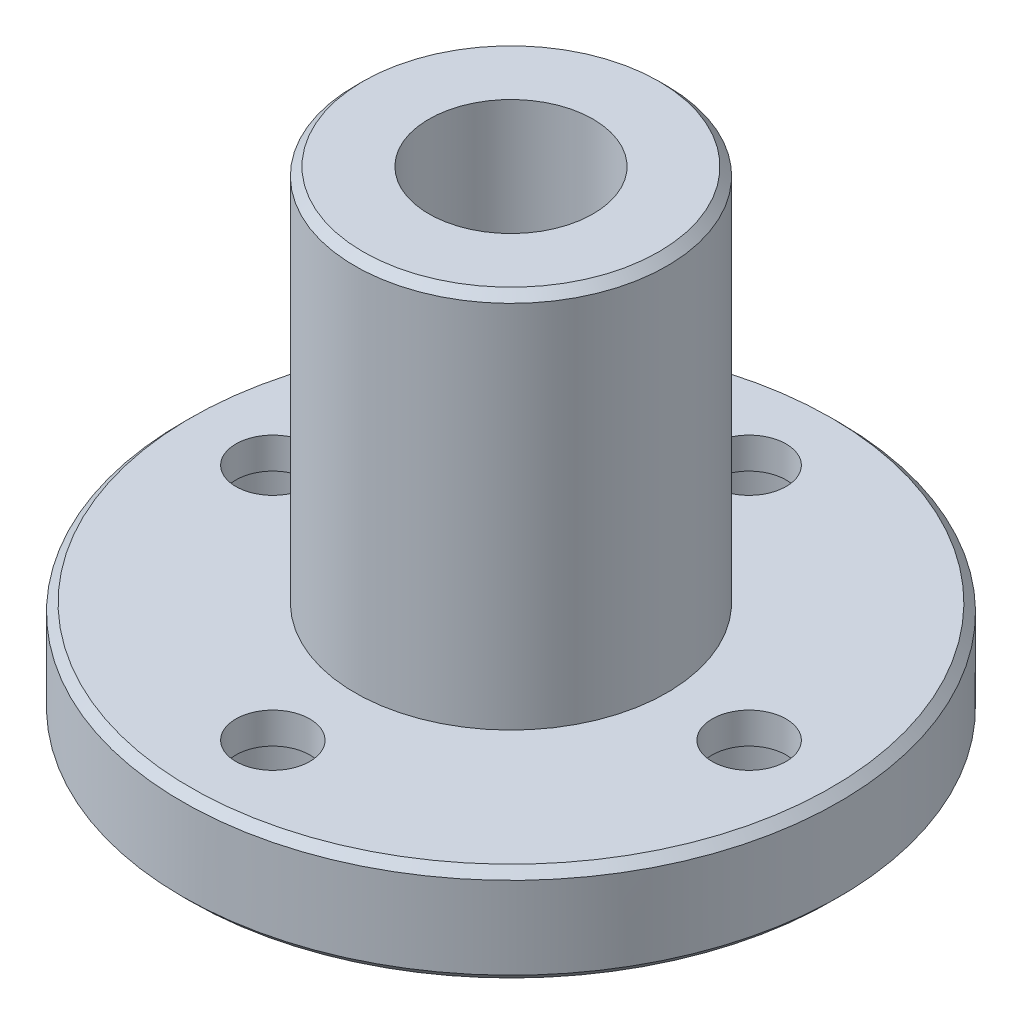
SolidWorks part; units mm, degrees
material "Простая углеродистая сталь"
ref_plane "Спереди" through (0, 0, 0) normal (0, 0, 1) x (1, 0, 0)
ref_plane "Сверху" through (0, 0, 0) normal (0, 1, 0) x (1, 0, 0)
ref_plane "Справа" through (0, 0, 0) normal (1, 0, 0) x (0, 0, -1)
sketch "Эскиз1" plane through (0, 0, 0) normal (0, 0, 1) x (1, 0, 0)
  line L0 (0, 0) -> (0, 30.6533) construction
  line L1 (-5, 0) -> (-20, 0)
  line L2 (-20, 0) -> (-20, 6)
  line L3 (-20, 6) -> (-9.5, 6)
  line L4 (-9.5, 6) -> (-9.5, 29)
  line L5 (-9.5, 29) -> (-5, 29)
  line L6 (-5, 29) -> (-5, 0)
  dimension "D1" = 10
  dimension "D2" = 40
  dimension "D3" = 6
  dimension "D4" = 19
  dimension "D5" = 29
revolve "Повернуть1" add sketch "Эскиз1" angle 360 about L0
sketch "Эскиз2" plane through (0, 0, 0) normal (0, -1, 0) x (1, 0, 0)
  circle A0 centre (0, 0) radius 14.5 construction
  circle A1 centre (0, 14.5) radius 2.25
  circle A2 centre (14.5, 0) radius 2.25
  circle A3 centre (0, -14.5) radius 2.25
  circle A4 centre (-14.5, 0) radius 2.25
  point P14 (0, 0)
  dimension "D1" = 29
  dimension "D2" = 4.5
  dimension "D3" = 4
extrude "Вырез-Вытянуть1" cut sketch "Эскиз2" against normal through all
sketch "Эскиз3" plane through (0, 0, 0) normal (0, -1, 0) x (1, 0, 0)
  circle A0 centre (0, 14.5) radius 3.75
  circle A1 centre (14.5, 0) radius 3.75
  circle A2 centre (0, -14.5) radius 3.75
  circle A3 centre (-14.5, 0) radius 3.75
  circle A4 centre (0, 0) radius 14.5 construction
  point P12 (0, 0)
  dimension "D1" = 7.5
  dimension "D2" = 4
extrude "Вырез-Вытянуть2" cut sketch "Эскиз3" against normal blind 4.1
chamfer "Фаска1" distance 0.5 angle 45 3 edges at (0, 29, -9.5) (0, 6, -20) (0, 0, -20)
